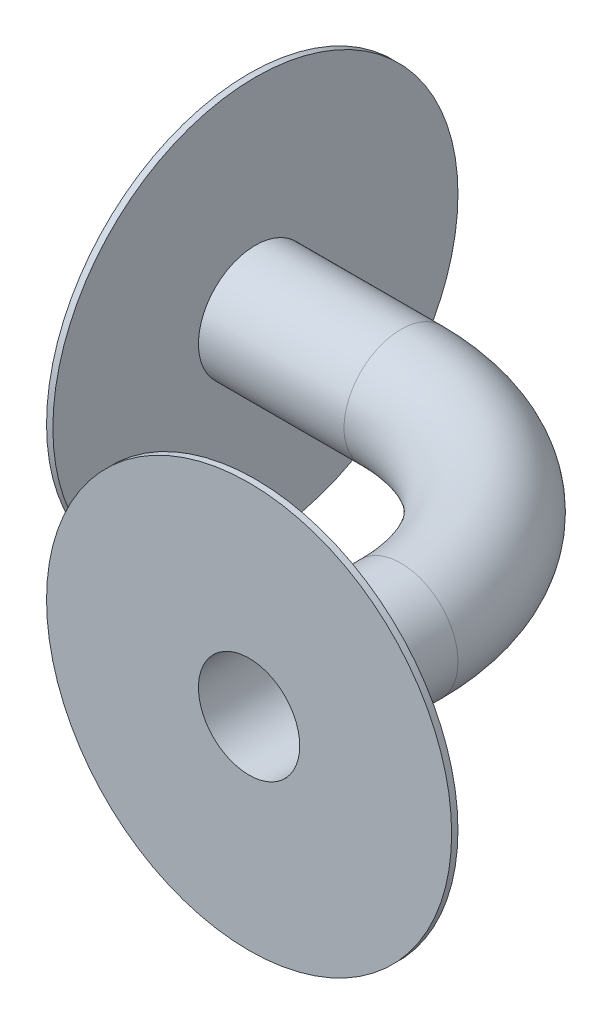
SolidWorks part; units mm, degrees
material "Copper"
ref_plane "Front Plane" through (0, 0, 0) normal (0, 0, 1) x (1, 0, 0)
ref_plane "Top Plane" through (0, 0, 0) normal (0, 1, 0) x (1, 0, 0)
ref_plane "Right Plane" through (0, 0, 0) normal (1, 0, 0) x (0, 0, -1)
sketch "Sketch1" plane through (0, 0, 0) normal (1, 0, 0) x (0, 0, -1)
  line L0 (-50.8, 0) -> (-50.8, 30.1607) construction
  circle A0 centre (0, 0) radius 12.7
  circle A1 centre (0, 0) radius 14.2875
  dimension "D1" = 25.4
  dimension "D2" = 28.575
  dimension "D3" = 50.8
revolve "Revolve1" add sketch "Sketch1" angle 90 about L0
sketch "Sketch2" plane through (0, 0, 50.8) normal (0, 0, 1) x (1, 0, 0)
  circle A0 centre (50.8, 0) radius 12.7 construction
  circle A1 centre (50.8, 0) radius 14.2875
  circle A2 centre (50.8, 0) radius 14.2875
  circle A3 centre (50.8, 0) radius 12.7
  dimension "D1" = 0
extrude "Boss-Extrude1" add sketch "Sketch2" along normal blind 38.1
sketch "Sketch3" plane through (0, 0, 0) normal (-1, 0, 0) x (0, 0, 1)
  circle A0 centre (0, 0) radius 12.7 construction
  circle A1 centre (0, 0) radius 14.2875
  circle A2 centre (0, 0) radius 14.2875
  circle A3 centre (0, 0) radius 12.7
  dimension "D1" = 0
extrude "Boss-Extrude2" add sketch "Sketch3" along normal blind 38.1
sketch "Sketch4" plane through (-38.1, 0, 0) normal (-1, 0, 0) x (0, 0, 1)
  circle A0 centre (0, 0) radius 12.7 construction
  circle A1 centre (0, 0) radius 12.7
  circle A2 centre (0, 0) radius 50.8
  dimension "D1" = 101.6
extrude "Boss-Extrude3" add sketch "Sketch4" against normal blind 1.5875
sketch "Sketch5" plane through (0, 0, 88.9) normal (0, 0, 1) x (1, 0, 0)
  circle A0 centre (50.8, 0) radius 12.7 construction
  circle A1 centre (50.8, 0) radius 12.7
  circle A2 centre (50.8, 0) radius 50.8
  dimension "D1" = 101.6
extrude "Boss-Extrude4" add sketch "Sketch5" against normal blind 1.5875
